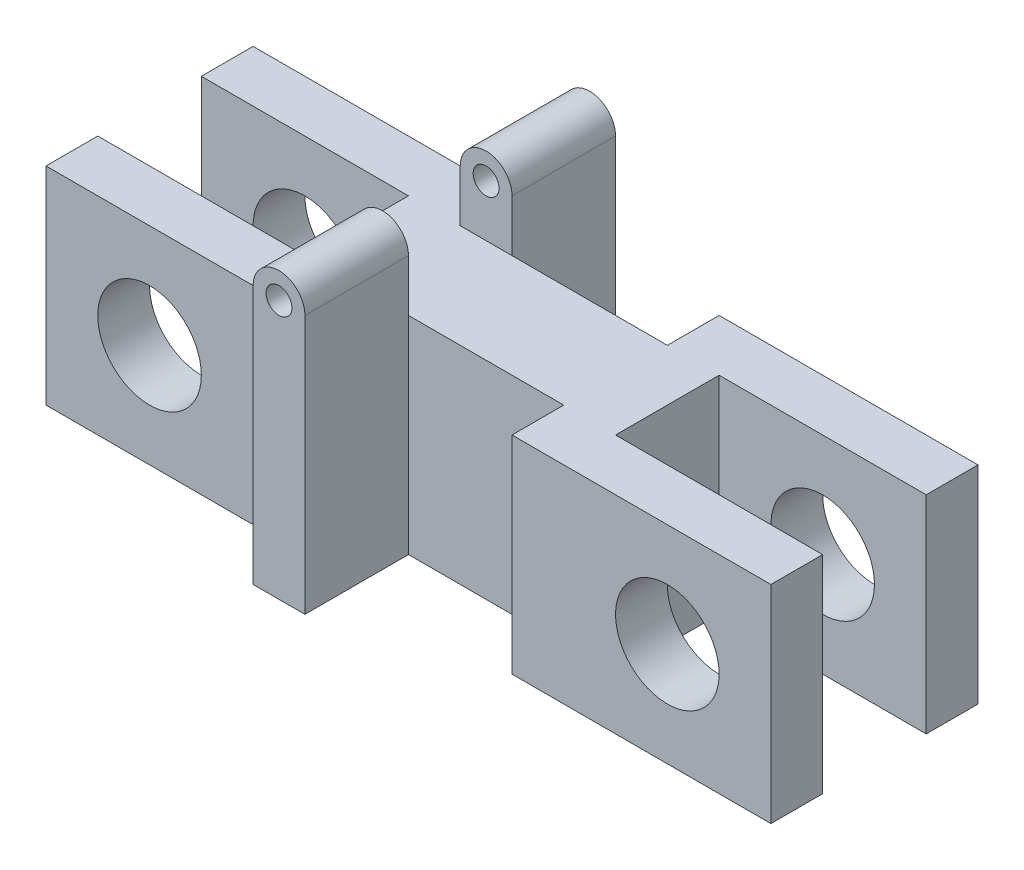
SolidWorks part; units mm, degrees
ref_plane "Front Plane" through (0, 0, 0) normal (0, 0, 1) x (1, 0, 0)
ref_plane "Top Plane" through (0, 0, 0) normal (0, 1, 0) x (1, 0, 0)
ref_plane "Right Plane" through (0, 0, 0) normal (1, 0, 0) x (0, 0, -1)
sketch "Sketch1" plane through (0, 0, 0) normal (0, 0, 1) x (1, 0, 0)
  line L1 (-35, -10) -> (35, -10)
  line L2 (-35, -10) -> (-35, 10)
  line L3 (-35, 10) -> (35, 10)
  line L4 (35, -10) -> (35, 10)
  line L5 (-35, -10) -> (35, 10) construction
  line L6 (-35, 10) -> (35, -10) construction
  point P0 (0, 0)
  dimension "D1" = 70
  dimension "D2" = 20
extrude "Boss-Extrude1" add sketch "Sketch1" along normal blind 20
sketch "Sketch2" plane through (-35, 0, 0) normal (-1, 0, 0) x (0, 0, 1)
  line L0 (20, 10) -> (0, 10) construction
  line L1 (5, -10) -> (15, -10)
  line L2 (5, -10) -> (5, 10)
  line L3 (5, 10) -> (15, 10)
  line L4 (15, -10) -> (15, 10)
  line L5 (5, -10) -> (15, 10) construction
  line L6 (5, 10) -> (15, -10) construction
  point P0 (10, 0)
  point P10 (10, 10)
  dimension "D1" = 10
extrude "Cut-Extrude1" cut sketch "Sketch2" against normal blind 20
sketch "Sketch3" plane through (0, 0, 20) normal (0, 0, 1) x (1, 0, 0)
  line L0 (-35, 10) -> (-35, -10) construction
  circle A0 centre (-25, 0) radius 5
  point P7 (-35, 0)
  dimension "D1" = 10
  dimension "D2" = 10
extrude "Cut-Extrude2" cut sketch "Sketch3" against normal blind 60
sketch "Sketch4" plane through (0, 0, 20) normal (0, 0, 1) x (1, 0, 0)
  line L0 (-10, -10) -> (0, -10)
  line L1 (-10, -10) -> (-10, 10)
  line L2 (-10, 10) -> (0, 10)
  line L3 (0, -10) -> (0, 10)
  line L4 (-10, -10) -> (0, 10) construction
  line L5 (-10, 10) -> (0, -10) construction
  line L6 (35, 10) -> (-35, 10) construction
  line L7 (-35, 10) -> (-35, -10) construction
  point P2 (-5, 0)
  dimension "D1" = 25
extrude "Cut-Extrude3" cut sketch "Sketch4" against normal blind 5
ref_plane "Plane1" through (0, 0, 10) normal (0, 0, 1) x (1, 0, 0)
mirror "Mirror2" about plane through (0, 0, 10) normal (0, 0, 1) of "Cut-Extrude3"
mirror "Mirror3" about plane through (0, 0, 0) normal (1, 0, 0) of "Mirror2", "Cut-Extrude1", "Cut-Extrude3", "Cut-Extrude2"
sketch "Sketch6" plane through (0, 0, 5) normal (0, 0, 1) x (1, 0, 0)
  point P0 (-25, 0)
  point P1 (25, 0)
sketch "Sketch7" plane through (0, 0, 15) normal (0, 0, 1) x (1, 0, 0)
  line L0 (-10, -10) -> (-10, 15)
  line L1 (-5, 15) -> (-5, -10)
  line L2 (10, 10) -> (-10, 10) construction
  line L4 (-10, 10) -> (-10, -10) construction
  line L5 (-10, 10) -> (-10, -10) construction
  line L6 (-10, -10) -> (10, -10) construction
  line L7 (-10, -10) -> (-5, -10)
  arc A0 (-10, 15) -> (-5, 15) centre (-7.5, 15) cw
  circle A1 centre (-7.5, 15) radius 1.25
  dimension "D1" = 5
  dimension "D2" = 2.5
  dimension "D3" = 2.5
extrude "Boss-Extrude2" add sketch "Sketch7" along normal blind 10 contours L1 L7 L0 A0 | A1
mirror "Mirror4" about plane through (0, 0, 10) normal (0, 0, 1) of "Boss-Extrude2"
